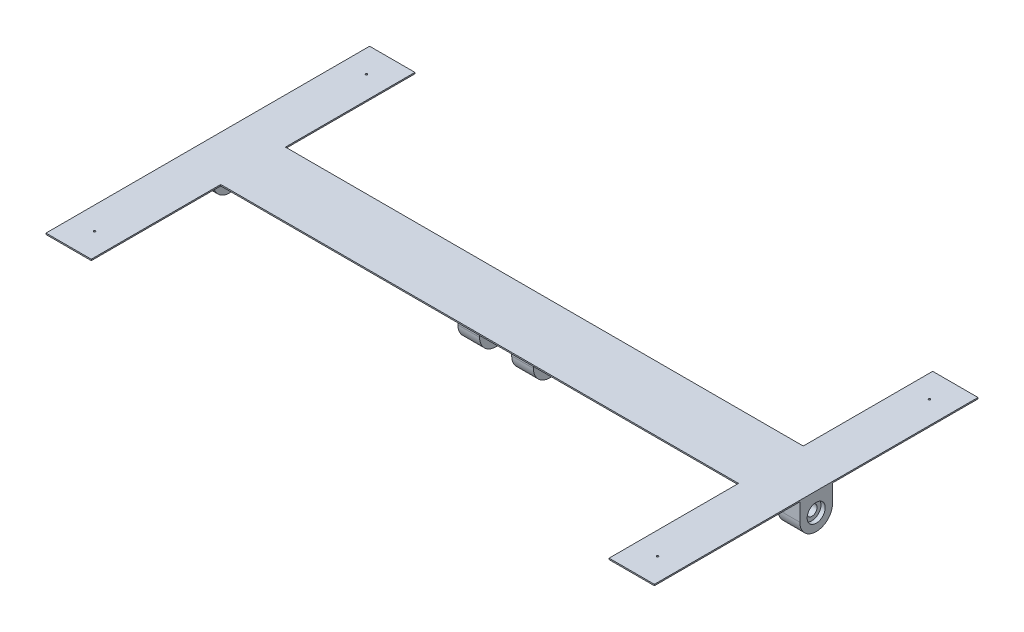
SolidWorks part; units mm, degrees
material "1023 Carbon Steel Sheet (SS)"
ref_plane "Front Plane" through (0, 0, 0) normal (0, 0, 1) x (1, 0, 0)
ref_plane "Top Plane" through (0, 0, 0) normal (0, 1, 0) x (1, 0, 0)
ref_plane "Right Plane" through (0, 0, 0) normal (1, 0, 0) x (0, 0, -1)
sketch "Sketch1" plane through (0, 0, 0) normal (0, 1, 0) x (1, 0, 0)
  line L0 (0, 1250) -> (4700, 1250) construction
  line L1 (0, 0) -> (4700, 0)
  line L2 (0, 0) -> (0, 2500)
  line L3 (0, 2500) -> (4700, 2500)
  line L4 (4700, 0) -> (4700, 2500)
  line L5 (350, 0) -> (4350, 0)
  line L6 (350, 0) -> (350, 1000)
  line L7 (350, 1000) -> (4350, 1000)
  line L8 (4350, 0) -> (4350, 1000)
  line L9 (4350, 2500) -> (4350, 1500)
  line L10 (350, 1500) -> (4350, 1500)
  line L11 (350, 2500) -> (350, 1500)
  line L12 (350, 2500) -> (4350, 2500)
  point P15 (2350, 1000)
  point P16 (2350, 1250)
  dimension "D1" = 2500
  dimension "D2" = 4700
  dimension "D3" = 1000
  dimension "D4" = 4000
extrude "Boss-Extrude1" add sketch "Sketch1" along normal blind 10 contours L2 L0 L4 L3 L9 L10 L11 | L0 L2 L1 L6 L7 L8 L4
sketch "Sketch3" plane through (0, 0, 0) normal (1, 0, 0) x (0, 0, -1)
  line L1 (1123.5, 0) -> (1376.5, 0)
  line L2 (1123.5, 0) -> (1123.5, -136.5)
  line L3 (1123.5, -136.5) -> (1376.5, -136.5)
  line L4 (1376.5, 0) -> (1376.5, -136.5)
  line L5 (0, 0) -> (2500, 0) construction
  line L6 (0, 0) -> (2500, 0)
  circle A0 centre (1250, -136.5) radius 126.5
  point P12 (1250, 0)
  dimension "D1" = 253
  dimension "D2" = 136.5
extrude "Boss-Extrude2" add sketch "Sketch3" along normal blind 168
ref_plane "Plane1" through (2350, 0, 0) normal (-1, 0, 0) x (0, 0, 1)
mirror "Mirror1" about plane through (2350, 0, 0) normal (-1, 0, 0) of "Boss-Extrude2"
sketch "Sketch6" plane through (168, 0, 0) normal (1, 0, 0) x (0, 0, -1)
  circle A0 centre (1250, -136.5) radius 70
  arc A1 (1123.5, -136.5) -> (1376.5, -136.5) centre (1250, -136.5) ccw construction
  dimension "D1" = 140
extrude "Cut-Extrude1" cut sketch "Sketch6" against normal blind 33
sketch "Sketch7" plane through (135, 0, 0) normal (1, 0, 0) x (0, 0, -1)
  circle A0 centre (1250, -136.5) radius 40
  circle A2 centre (1250, -136.5) radius 70 construction
  dimension "D1" = 80
extrude "Cut-Extrude2" cut sketch "Sketch7" against normal through all
sketch "Sketch9" plane through (0, 0, 0) normal (-1, 0, 0) x (0, 0, 1)
  circle A0 centre (-1250, -136.5) radius 70
  dimension "D1" = 140
extrude "Cut-Extrude4" cut sketch "Sketch9" against normal blind 33
mirror "Mirror2" about plane through (2350, 0, 0) normal (-1, 0, 0) of "Cut-Extrude4", "Cut-Extrude2", "Cut-Extrude1"
sketch "Sketch8" plane through (0, 10, 0) normal (0, 1, 0) x (1, 0, 0)
  line L0 (4350, 2500) -> (4700, 2500) construction
  line L1 (4350, 2500) -> (4700, 2500)
  line L2 (4350, 0) -> (4700, 0) construction
  circle A0 centre (4525, 2300) radius 7
  circle A1 centre (4525, 200) radius 7
  point P5 (4525, 2500)
  dimension "D1" = 14
  dimension "D3" = 14
  dimension "D2" = 200
  dimension "D4" = 200
extrude "Cut-Extrude3" cut sketch "Sketch8" against normal through all contours A0 | A1
mirror "Mirror3" about plane through (2350, 0, 0) normal (-1, 0, 0) of "Cut-Extrude3"
pattern_linear "LPattern1" count 2 spacing 2058 along (1, 0, 0) of "Cut-Extrude1", "Cut-Extrude2", "Boss-Extrude2", "Cut-Extrude4"
mirror "Mirror4" about plane through (2350, 0, 0) normal (-1, 0, 0) of "LPattern1", "Boss-Extrude2", "Cut-Extrude1", "Cut-Extrude2", "Cut-Extrude4"
equation "\"Width\"= 2.5m"
equation "\"Length\"= 4.7m"
equation "\"thick\"= 0.01m"
equation "\"bolt_dia\"= 8"
equation "\"D1@Sketch1\"=\"Width\""
equation "\"D2@Sketch1\"=\"Length\""
equation "\"D1@Boss-Extrude1\"=\"thick\""
equation "\"gear-dia\"= 10cm"
equation "\"str\"=150"
equation "\"D1@Sketch3\"=\"sprocket\" +10"
equation "\"outer_bearing\"= 140"
equation "\"inner_bearing\"= 80"
equation "\"thick_bearing\"= 33"
equation "\"D2@Sketch3\"= \"D1@Sketch3\" / 2 + 10"
equation "\"D1@Sketch6\"=\"outer_bearing\""
equation "\"D1@Cut-Extrude1\"=\"thick_bearing\""
equation "\"D1@Sketch7\"=\"inner_bearing\""
equation "\"sprocket\"= 243"
equation "\"D1@Sketch9\"=\"outer_bearing\""
equation "\"D1@Cut-Extrude4\"=\"thick_bearing\""
